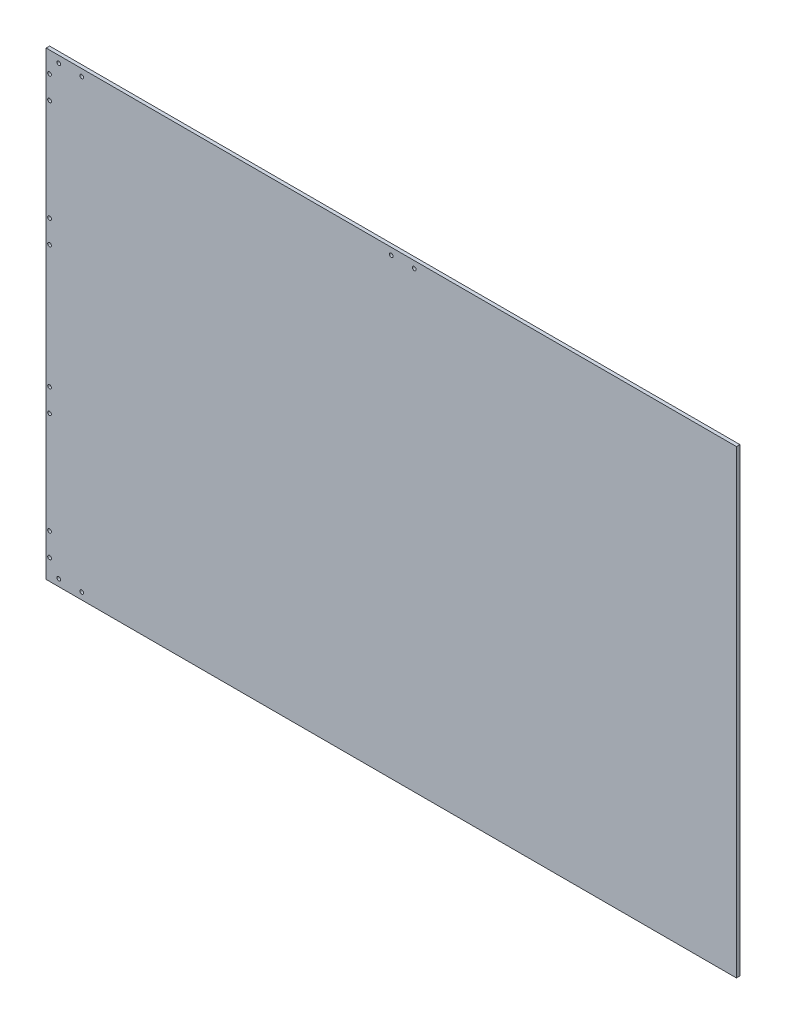
SolidWorks part; units mm, degrees
ref_plane "前视基准面" through (0, 0, 0) normal (0, 0, 1) x (1, 0, 0)
ref_plane "上视基准面" through (0, 0, 0) normal (0, 1, 0) x (1, 0, 0)
ref_plane "右视基准面" through (0, 0, 0) normal (1, 0, 0) x (0, 0, -1)
other "Configuration Table"
sketch "草图1" plane through (0, 0, 0) normal (0, 0, 1) x (1, 0, 0)
  line L1 (-300, 200) -> (300, 200)
  line L2 (-300, 200) -> (-300, -200)
  line L3 (-300, -200) -> (300, -200)
  line L4 (300, 200) -> (300, -200)
  line L5 (-300, 200) -> (300, -200) construction
  line L6 (-300, -200) -> (300, 200) construction
  point P0 (0, 0)
  dimension "D1" = 600
  dimension "D2" = 400
extrude "凸台-拉伸1" add sketch "草图1" along normal blind 3
sketch "草图3" plane through (0, 0, 0) normal (0, 0, -1) x (-1, 0, 0)
  circle A0 centre (269, -194) radius 1.6
  circle A1 centre (289, -194) radius 1.6
  circle A2 centre (297, -182) radius 1.6
  circle A3 centre (297, -162) radius 1.6
  circle A4 centre (297, 162) radius 1.6
  circle A5 centre (297, 182) radius 1.6
  circle A6 centre (289, 194) radius 1.6
  circle A7 centre (269, 194) radius 1.6
  dimension "D1" = 3.2
extrude "切除-拉伸1" cut sketch "草图3" against normal through all
sketch "草图4" plane through (0, 0, 0) normal (0, 0, -1) x (-1, 0, 0)
  circle A0 centre (0, 194) radius 1.6
  circle A1 centre (-20, 194) radius 1.6
  circle A2 centre (0, 194) radius 1.5 construction
  dimension "D1" = 3.2
extrude "切除-拉伸2" cut sketch "草图4" against normal through all
sketch "草图5" plane through (0, 0, 3) normal (0, 0, 1) x (1, 0, 0)
  circle A0 centre (-297, 73.5) radius 1.6
  circle A1 centre (-297, 53.5) radius 1.6
  circle A2 centre (-297, -53.5) radius 1.6
  circle A3 centre (-297, -73.5) radius 1.6
  dimension "D1" = 3.2
extrude "切除-拉伸3" cut sketch "草图5" against normal through all
